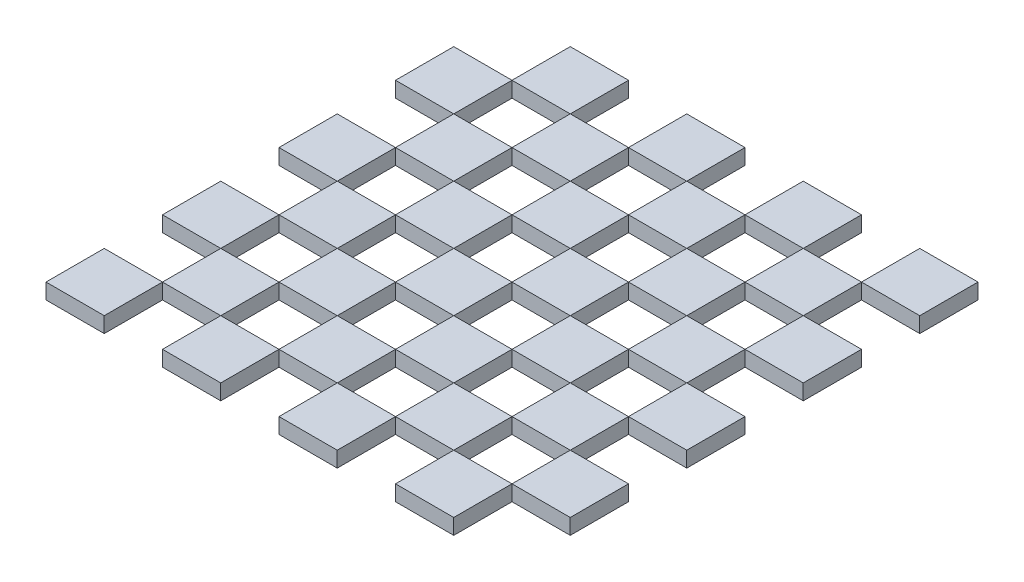
SolidWorks part; units mm, degrees
material "Plain Carbon Steel"
ref_plane "Front Plane" through (0, 0, 0) normal (0, 0, 1) x (1, 0, 0)
ref_plane "Top Plane" through (0, 0, 0) normal (0, 1, 0) x (1, 0, 0)
ref_plane "Right Plane" through (0, 0, 0) normal (1, 0, 0) x (0, 0, -1)
sketch "Sketch1" plane through (0, 0, 0) normal (0, 1, 0) x (1, 0, 0)
  line L0 (0, 150) -> (0, -150)
  line L1 (-150, -150) -> (150, -150)
  line L2 (-150, -150) -> (-150, 150)
  line L3 (-150, 150) -> (150, 150)
  line L4 (150, -150) -> (150, 150)
  line L5 (-150, -150) -> (150, 150) construction
  line L6 (-150, 150) -> (150, -150) construction
  line L7 (-112.5, 150) -> (-112.5, -150)
  line L8 (37.5, 150) -> (37.5, -150)
  line L9 (-75, 150) -> (-75, -150)
  line L10 (-37.5, 150) -> (-37.5, -150)
  line L11 (75, 150) -> (75, -150)
  line L12 (112.5, 150) -> (112.5, -150)
  line L13 (-150, -75) -> (150, -75)
  line L14 (-150, 37.5) -> (150, 37.5)
  line L15 (-150, 75) -> (150, 75)
  line L16 (-150, -112.5) -> (150, -112.5)
  line L17 (-150, 0) -> (150, 0)
  line L18 (-150, -37.5) -> (150, -37.5)
  line L19 (-150, 112.5) -> (150, 112.5)
  point P0 (0, 0)
  point P20 (0, 0)
  point P35 (-150, 116.087)
  point P36 (-150, 89.5251)
  point P37 (150, 89.5251)
  point P38 (150, 57.7454)
  point P39 (150, 24.5505)
  point P40 (0, 0)
  point P41 (-150, 31.9565)
  point P42 (-150, -29.3478)
  point P43 (150, -34.5652)
  point P44 (-150, -67.1739)
  point P45 (150, -69.7826)
  point P46 (150, -103.0435)
  point P47 (-150, -111.5217)
  dimension "D1" = 300
  dimension "D2" = 37.5
  dimension "D3" = 37.5
  dimension "D4" = 37.5
  dimension "D5" = 37.5
  dimension "D6" = 37.5
  dimension "D7" = 37.5
  dimension "D8" = 37.5
  dimension "D9" = 37.5
  dimension "D10" = 37.5
  dimension "D11" = 37.5
  dimension "D12" = 37.5
  dimension "D13" = 37.5
extrude "Boss-Extrude1" add sketch "Sketch1" along normal blind 10 contours L16 L2 L1 L7 | L16 L9 L1 L10 | L16 L0 L1 L8 | L16 L11 L1 L12 | L12 L16 L4 L13 | L12 L18 L4 L17 | L15 L12 L14 L4 | L12 L19 L4 L3 | L19 L11 L15 L12 | L11 L17 L12 L14 | L18 L11 L13 L12 | L8 L16 L11 L13 | L8 L18 L11 L17 | L15 L8 L14 L11 | L8 L19 L11 L3 | L19 L0 L15 L8 | L0 L17 L8 L14 | L18 L0 L13 L8 | L10 L16 L0 L13 | L10 L18 L0 L17 | L15 L10 L14 L0 | L10 L19 L0 L3 | L7 L19 L9 L3 | L19 L2 L15 L7 | L19 L9 L15 L10 | L15 L7 L14 L9 | L9 L17 L10 L14 | L2 L17 L7 L14 | L7 L18 L9 L17 | L18 L2 L13 L7 | L18 L9 L13 L10 | L7 L16 L9 L13
